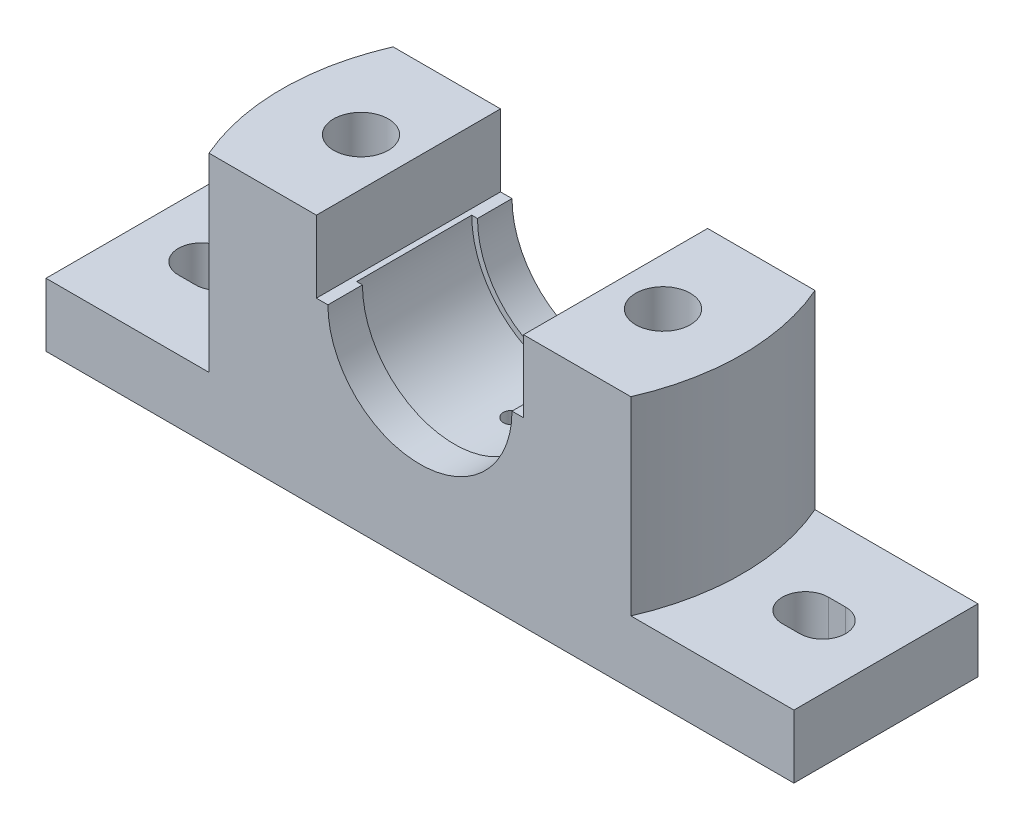
SolidWorks part; units mm, degrees
ref_plane "Front Plane" through (0, 0, 0) normal (0, 0, 1) x (1, 0, 0)
ref_plane "Top Plane" through (0, 0, 0) normal (0, 1, 0) x (1, 0, 0)
ref_plane "Right Plane" through (0, 0, 0) normal (1, 0, 0) x (0, 0, -1)
sketch "Sketch1" plane through (0, 0, 0) normal (0, 1, 0) x (1, 0, 0)
  line L0 (-102, 0) -> (-108, 0) construction
  line L1 (130, -32) -> (-130, -32)
  line L2 (130, -32) -> (130, 32)
  line L3 (130, 32) -> (-130, 32)
  line L4 (-130, -32) -> (-130, 32)
  line L5 (130, -32) -> (-130, 32) construction
  line L6 (130, 32) -> (-130, -32) construction
  line L7 (-102, -8) -> (-108, -8)
  line L8 (-102, 8) -> (-108, 8)
  line L9 (0, -41.1491) -> (0, 62.55) construction
  line L10 (102, 0) -> (108, 0) construction
  line L11 (102, -8) -> (108, -8)
  line L12 (102, 8) -> (108, 8)
  arc A0 (-102, -8) -> (-102, 8) centre (-102, 0) ccw
  arc A1 (-108, 8) -> (-108, -8) centre (-108, 0) ccw
  arc A2 (102, -8) -> (102, 8) centre (102, 0) cw
  arc A3 (108, 8) -> (108, -8) centre (108, 0) cw
  point P0 (0, 0)
  point P8 (-105, 0)
  point P18 (105, 0)
  point P23 (-116, 0)
  point P24 (-94, 0)
  point P25 (-105, 8)
  dimension "D1" = 64
  dimension "D2" = 22
  dimension "D3" = 16
  dimension "D4" = 25
  dimension "D5" = 210
extrude "Boss-Extrude1" add sketch "Sketch1" along normal blind 22
ref_plane "Plane1" through (0, 88, 0) normal (0, -1, 0) x (-1, 0, 0)
sketch "Sketch3" plane through (0, 88, 0) normal (0, -1, 0) x (-1, 0, 0)
  line L0 (-130, 32) -> (130, 32) construction
  line L1 (73.3212, -32) -> (-73.3212, -32)
  line L3 (73.3212, 32) -> (-73.3212, 32)
  line L5 (73.3212, -32) -> (-73.3212, 32) construction
  line L6 (73.3212, 32) -> (-73.3212, -32) construction
  line L7 (0, 55) -> (0, -55) construction
  arc A1 (-73.3212, 32) -> (-73.3212, -32) centre (0, 0) ccw
  circle A2 centre (-52.5, 0) radius 9.5
  circle A3 centre (52.5, 0) radius 9.5
  arc A4 (73.3212, 32) -> (73.3212, -32) centre (0, 0) cw
  point P0 (0, 0)
  dimension "D1" = 80
  dimension "D2" = 19
  dimension "D3" = 105
extrude "Boss-Extrude2" add sketch "Sketch3" along normal up to surface (66 mm away) up to face at (0, 22, 0)
sketch "Sketch5" plane through (0, 0, 32) normal (0, 0, 1) x (1, 0, 0)
  line L0 (0, 0) -> (0, 153.856) construction
  line L1 (157.184, 63) -> (-157.184, 63) construction
  line L2 (-36, 63) -> (-32, 63)
  line L4 (-36, 63) -> (-36, 88)
  line L5 (73.3212, 88) -> (-73.3212, 88) construction
  line L6 (0, 31) -> (0, 88)
  line L7 (-36, 88) -> (0, 88)
  arc A0 (-32, 63) -> (0, 31) centre (0, 63) ccw
  point P6 (0, 63)
  dimension "D2" = 32
  dimension "D1" = 63
  dimension "D3" = 36
extrude "Cut-Extrude2" cut sketch "Sketch5" against normal blind 75
sketch "Sketch6" plane through (0, 0, 0) normal (0, 0, 1) x (1, 0, 0)
  line L0 (-36, 63) -> (-32, 63) construction
  line L1 (0, 0) -> (0, 153.856) construction
  line L2 (-34, 63) -> (0, 63)
  line L3 (0, 63) -> (0, 29)
  arc A0 (-34, 63) -> (0, 29) centre (0, 63) ccw
extrude "Cut-Extrude3" cut sketch "Sketch6" against normal mid plane 40
mirror "Mirror1" about plane through (0, 0, 0) normal (1, 0, 0) of "Cut-Extrude3", "Cut-Extrude2"
ref_plane "Plane2" through (0, 29, 0) normal (0, 1, 0) x (1, 0, 0)
sketch "Sketch7" plane through (0, 29, 0) normal (0, 1, 0) x (1, 0, 0)
  circle A0 centre (0, 0) radius 3
  dimension "D1" = 6
extrude "Cut-Extrude5" cut sketch "Sketch7" against normal blind 6 and the other way blind 40
sketch "Sketch8" plane through (0, 0, 0) normal (0, -1, 0) x (1, 0, 0)
  line L0 (-130, 32) -> (130, 32) construction
  line L1 (73.3212, -20) -> (6, -20)
  line L2 (73.3212, -20) -> (73.3212, 20)
  line L3 (73.3212, 20) -> (6, 20)
  line L4 (6, -20) -> (6, 20)
  line L5 (73.3212, -20) -> (6, 20) construction
  line L6 (73.3212, 20) -> (6, -20) construction
  point P0 (39.6606, 0)
  point P8 (0, 0)
  point P9 (0, 0)
  dimension "D1" = 40
  dimension "D2" = 32
  dimension "D3" = 6
extrude "Cut-Extrude6" cut sketch "Sketch8" against normal blind 2
mirror "Mirror2" about plane through (0, 0, 0) normal (1, 0, 0) of "Cut-Extrude6"
sketch "Sketch9" plane through (0, 22, 0) normal (0, 1, 0) x (1, 0, 0)
  circle A0 centre (-52.5, 0) radius 9.5 construction
  circle A1 centre (-52.5, 0) radius 9.5
  circle A2 centre (52.5, 0) radius 9.5 construction
  circle A3 centre (52.5, 0) radius 9.5
extrude "Cut-Extrude7" cut sketch "Sketch9" against normal blind 45
